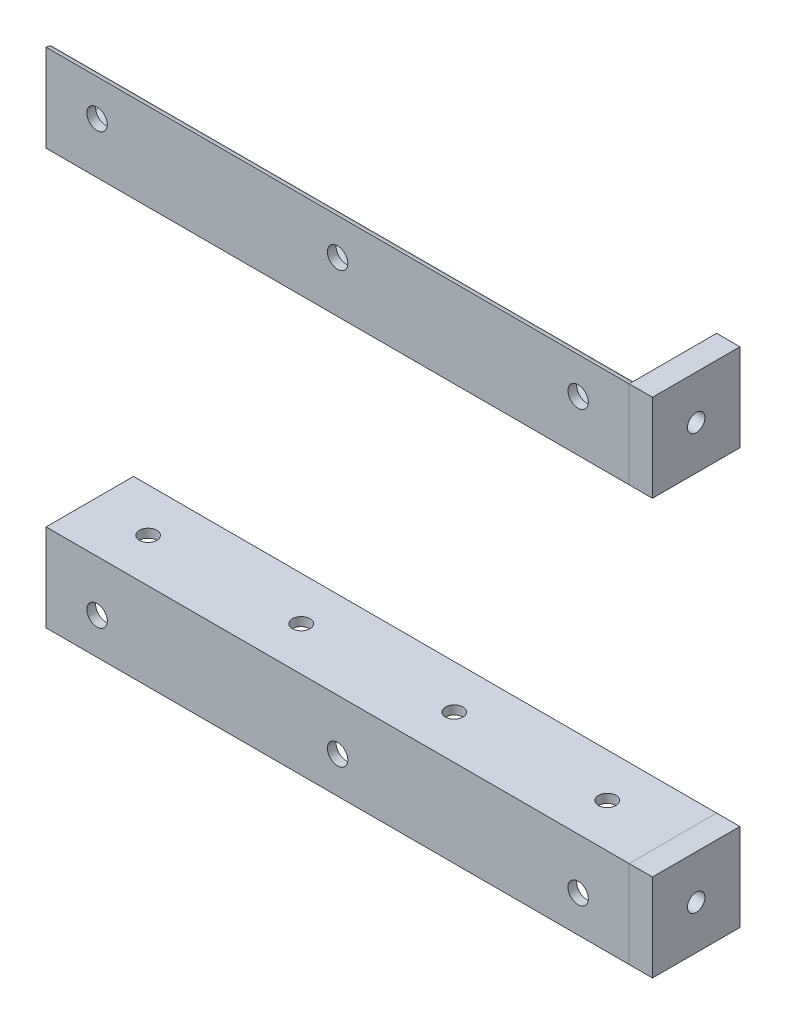
SolidWorks part; units mm, degrees
ref_plane "前视基准面" through (0, 0, 0) normal (0, 0, 1) x (1, 0, 0)
ref_plane "上视基准面" through (0, 0, 0) normal (0, 1, 0) x (1, 0, 0)
ref_plane "右视基准面" through (0, 0, 0) normal (1, 0, 0) x (0, 0, -1)
sketch3d "3D草图1"
  line L0 (0, 0, 0) -> (400, 0, 0)
  line L1 (0, 225, 0) -> (400, 225, 0)
  line L2 (0, 225, 0) -> (0, 0, 0)
  dimension "D1" = 225
  dimension "D2" = 400
  dimension "D3" = 400
other "Gbt 706-2008 热轧型钢_等边角钢 60×60×6(1)"
ref_plane "基准面1" through (0, 225, 0) normal (1, 0, 0) x (0, 0, -1)
sketch "Sketch13" plane through (0, 225, 0) normal (1, 0, 0) x (0, 0, -1)
  line L0 (0, 60) -> (0, 0)
  line L1 (0, 0) -> (60, 0)
  line L2 (54, 6) -> (12.5, 6)
  line L3 (6, 12.5) -> (6, 54)
  arc A0 (60, 0) -> (54, 6) centre (54, 0) ccw
  arc A1 (12.5, 6) -> (6, 12.5) centre (12.5, 12.5) cw
  arc A2 (6, 54) -> (0, 60) centre (0, 54) ccw
  point P10 (0, 60)
  point P11 (0, 0)
  point P12 (0, 30)
  point P13 (30, 0)
  point P14 (60, 0)
  point P15 (60, 60)
  point P16 (30, 60)
  point P17 (60, 30)
  point P18 (6, 30)
  point P19 (30, 6)
  point P20 (30, 30)
  point P21 (0, 0)
  point P23 (6, 60)
  point P24 (60, 6)
  dimension "R" = 6.5
  dimension "b" = 60
  dimension "d" = 6
other "Gbt 706-2008 热轧型钢_等边角钢 60×60×6(2)"
ref_plane "基准面2" through (0, 0, 0) normal (1, 0, 0) x (0, -1, 0)
sketch "Sketch1" plane through (0, 0, 0) normal (1, 0, 0) x (0, -1, 0)
  line L0 (0, 60) -> (0, 0)
  line L1 (0, 0) -> (60, 0)
  line L2 (54, 6) -> (12.5, 6)
  line L3 (6, 12.5) -> (6, 54)
  arc A0 (60, 0) -> (54, 6) centre (54, 0) ccw
  arc A1 (12.5, 6) -> (6, 12.5) centre (12.5, 12.5) cw
  arc A2 (6, 54) -> (0, 60) centre (0, 54) ccw
  point P10 (0, 60)
  point P11 (0, 0)
  point P12 (0, 30)
  point P13 (30, 0)
  point P14 (60, 0)
  point P15 (60, 60)
  point P16 (30, 60)
  point P17 (60, 30)
  point P18 (6, 30)
  point P19 (30, 6)
  point P20 (30, 30)
  point P21 (0, 0)
  point P23 (6, 60)
  point P24 (60, 6)
  dimension "R" = 6.5
  dimension "b" = 60
  dimension "d" = 6
other "Gbt 706-2008 热轧型钢_等边角钢 60×60×6(3)"
ref_plane "基准面3" through (0, 225, 0) normal (0, -1, 0) x (-1, 0, 0)
sketch "Sketch14" plane through (0, 225, 0) normal (0, -1, 0) x (-1, 0, 0)
  line L0 (0, 60) -> (0, 0)
  line L1 (0, 0) -> (60, 0)
  line L2 (54, 6) -> (12.5, 6)
  line L3 (6, 12.5) -> (6, 54)
  arc A0 (60, 0) -> (54, 6) centre (54, 0) ccw
  arc A1 (12.5, 6) -> (6, 12.5) centre (12.5, 12.5) cw
  arc A2 (6, 54) -> (0, 60) centre (0, 54) ccw
  point P10 (0, 60)
  point P11 (0, 0)
  point P12 (0, 30)
  point P13 (30, 0)
  point P14 (60, 0)
  point P15 (60, 60)
  point P16 (30, 60)
  point P17 (60, 30)
  point P18 (6, 30)
  point P19 (30, 6)
  point P20 (30, 30)
  point P21 (0, 0)
  point P23 (6, 60)
  point P24 (60, 6)
  dimension "R" = 6.5
  dimension "b" = 60
  dimension "d" = 6
sketch "草图8" plane through (400, 0, 0) normal (1, 0, 0) x (0, 0, -1)
  line L0 (0, 285) -> (0, 225)
  line L1 (0, 225) -> (60, 225)
  line L2 (60, 225) -> (60, 285)
  line L3 (60, 285) -> (0, 285)
  line L4 (0, 0) -> (60, 0)
  line L5 (0, 0) -> (0, -60)
  line L6 (0, -60) -> (60, -60)
  line L7 (60, -60) -> (60, 0)
  arc A0 (0, -60) -> (6, -54) centre (0, -54) ccw construction
extrude "凸台-拉伸2" add sketch "草图8" along normal blind 16 separate body
hole_wizard "M14 螺纹孔2" positions "草图9" profile "草图10" tap size "M14" standard "GB"
sketch "草图9" plane through (416, 0, 0) normal (1, 0, 0) x (0, 0, -1)
  line L0 (60, -60) -> (60, 0) construction
  line L1 (0, -60) -> (60, -60) construction
  line L2 (0, 225) -> (60, 225) construction
  line L3 (0, 285) -> (0, 225) construction
  point P0 (30, 255)
  point P2 (30, -30)
  point P9 (30, -60)
  point P12 (30, 225)
  dimension "D1" = 30
  dimension "D2" = 30
  dimension "D3" = 30
  dimension "D4" = 30
sketch "草图10" plane through (416, 255, -30) normal (0, 1, 0) x (0, 0, -1)
  line L0 (0, 0) -> (0, 41.6052)
  line L1 (0, 41.6052) -> (6, 38)
  line L2 (6, 38) -> (6, 0)
  line L5 (6, 0) -> (0, 0)
  line L10 (0, 41.6052) -> (-6, 38) construction
  line L11 (0, -6.35) -> (0, 107.95) construction
  dimension "螺纹孔钻头直径" = 12
  dimension "螺纹孔钻头深度" = 38
  dimension "导头角度" = 118
cosmetic thread "孔螺蚊线3" parameters "D1"=16, "D2"=14
cosmetic thread "孔螺蚊线4" parameters "D1"=16, "D2"=14
hole_wizard "Ø12.0 (12) 直径孔1" positions "草图11" profile "草图12" hole size "Ø12.0" standard "GB" end condition through all
sketch "草图11" plane through (0, -6, 0) normal (0, -1, 0) x (1, 0, 0)
  line L0 (400, -12.5) -> (400, -54) construction
  line L1 (0, -12.5) -> (0, -54) construction
  line L2 (400, -60) -> (0, -60) construction
  point P0 (355, -30)
  point P2 (250, -30)
  point P4 (145, -30)
  point P6 (40, -30)
  dimension "D1" = 45
  dimension "D2" = 105
  dimension "D3" = 105
  dimension "D4" = 40
  dimension "D5" = 30
sketch "草图12" plane through (355, -6, -30) normal (1, 0, 0) x (0, 0, -1)
  line L0 (0, 0) -> (0, 291)
  line L1 (0, 291) -> (6, 291)
  line L2 (6, 291) -> (6, 0)
  line L5 (6, 0) -> (0, 0)
  line L11 (0, -6.35) -> (0, 107.95) construction
  dimension "通孔孔直径" = 12
  dimension "通孔孔深度" = 291
hole_wizard "Ø14.0 (14) 直径孔1" positions "草图13" profile "草图14" hole size "Ø14.0" standard "GB" end condition through all
sketch "草图13" plane through (0, 0, -6) normal (0, 0, -1) x (-1, 0, 0)
  line L0 (60, 112.5) -> (-529.5786, 112.5) construction
  line L1 (60, 0) -> (60, 225) construction
  line L3 (-400, 237.5) -> (-400, 279) construction
  line L4 (0, 237.5) -> (0, 279) construction
  line L5 (-400, 285) -> (0, 285) construction
  line L6 (54, 225) -> (12.5, 225) construction
  point P0 (-365, 260)
  point P2 (-200, 260)
  point P4 (-35, 260)
  point P6 (-365, -35)
  point P8 (-200, -35)
  point P10 (-35, -35)
  point P12 (35, 185)
  point P14 (35, 40)
  point P24 (-400, 258.25)
  point P27 (0, 258.25)
  dimension "D1" = 35
  dimension "D2" = 35
  dimension "D3" = 25
  dimension "D4" = 165
  dimension "D5" = 25
  dimension "D6" = 40
sketch "草图14" plane through (365, 260, -6) normal (1, 0, 0) x (0, 1, 0)
  line L0 (0, 0) -> (0, 6)
  line L1 (0, 6) -> (7, 6)
  line L2 (7, 6) -> (7, 0)
  line L5 (7, 0) -> (0, 0)
  line L11 (0, -6.35) -> (0, 107.95) construction
  dimension "通孔孔直径" = 14
  dimension "通孔孔深度" = 6
sketch "草图15" plane through (0, 0, 0) normal (1, 0, 0) x (0, 0, -1)
  line L1 (0, 0) -> (60, 0)
  line L2 (0, 0) -> (0, 225)
  line L3 (0, 225) -> (60, 225)
  line L4 (60, 0) -> (60, 225)
extrude "切除-拉伸1" cut sketch "草图15" against normal blind 100
